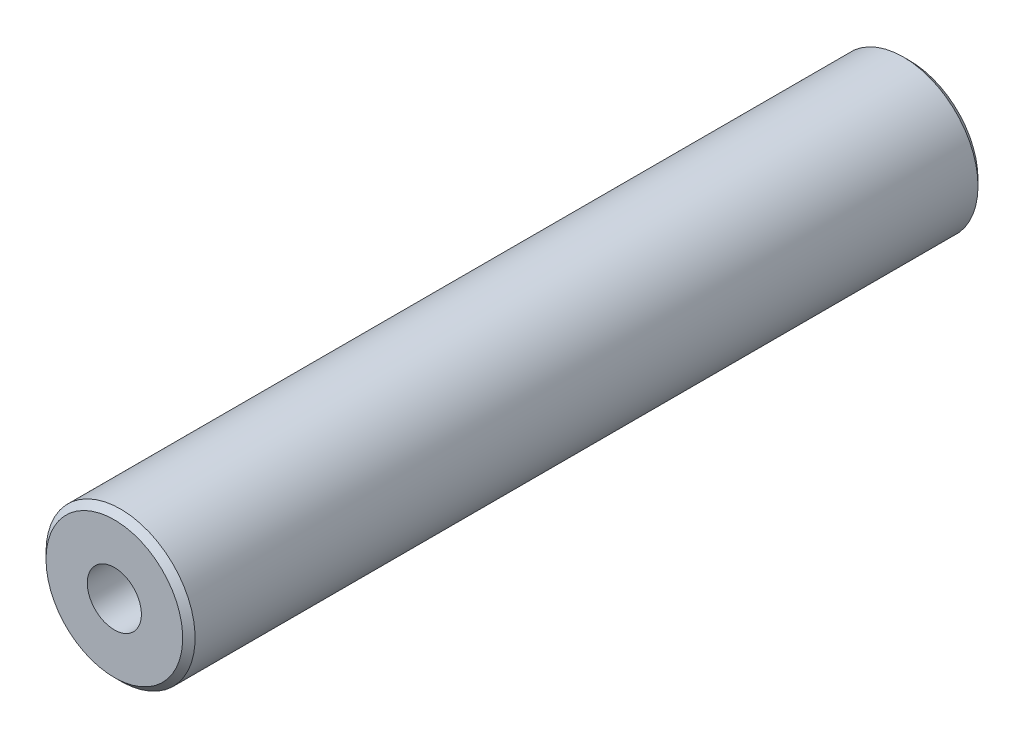
SolidWorks part; units mm, degrees
material "Alloy Steel (SS)"
ref_plane "Front Plane" through (0, 0, 0) normal (0, 0, 1) x (1, 0, 0)
ref_plane "Top Plane" through (0, 0, 0) normal (0, 1, 0) x (1, 0, 0)
ref_plane "Right Plane" through (0, 0, 0) normal (1, 0, 0) x (0, 0, -1)
sketch "Sketch1" plane through (0, 0, 0) normal (0, 0, 1) x (1, 0, 0)
  circle A0 centre (0, 0) radius 4.7625
  dimension "D1" = 9.525
extrude "Boss-Extrude1" add sketch "Sketch1" along normal mid plane 50.8
hole_wizard "Tap Drill for #8-32 Tap1" positions "3DSketch1" profile "Sketch2" hole size "#8-32" standard "ANSI Inch"
sketch3d "3DSketch1"
  line L0 (0, 0, 25.4) -> (0, 0, -25.4) construction
  point P0 (0, 0, 25.4)
  point P4 (0, 0, -25.4)
sketch "Sketch2" plane through (0, 0, 25.4) normal (1, 0, 0) x (0, -1, 0)
  line L0 (0, 0) -> (0, 7.3878)
  line L1 (0, 7.3878) -> (1.7272, 6.35)
  line L2 (1.7272, 6.35) -> (1.7272, 0)
  line L5 (1.7272, 0) -> (0, 0)
  line L10 (0, 7.3878) -> (-1.7272, 6.35) construction
  line L11 (0, -6.35) -> (0, 107.95) construction
  dimension "Hole Dia." = 3.4544
  dimension "Hole Depth" = 6.35
  dimension "Drill Angle" = 118
chamfer "Chamfer1" distance 0.3969 angle 45 2 edges at (4.7625, 0, -25.4) (4.7625, 0, 25.4)
